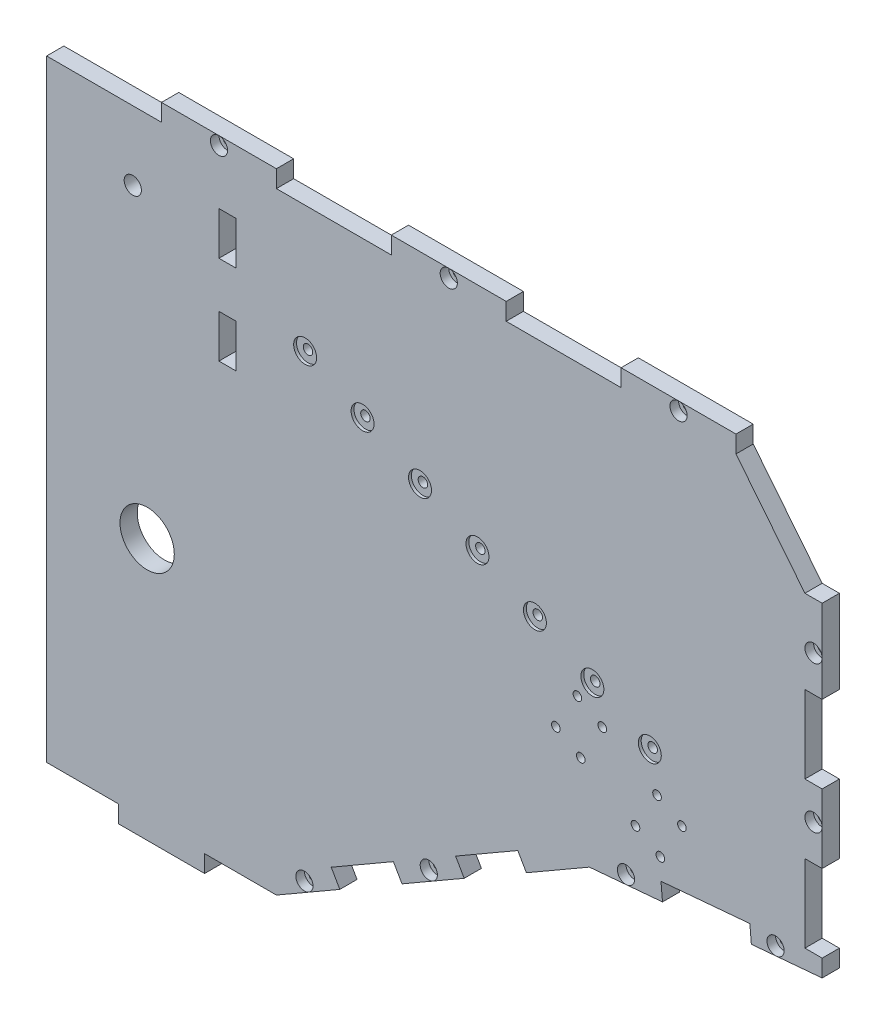
SolidWorks part; units mm, degrees
ref_plane "Plan de face" through (0, 0, 0) normal (0, 0, 1) x (1, 0, 0)
ref_plane "Plan de dessus" through (0, 0, 0) normal (0, 1, 0) x (1, 0, 0)
ref_plane "Plan de droite" through (0, 0, 0) normal (1, 0, 0) x (0, 0, -1)
sketch "Esquisse1" plane through (0, 0, 0) normal (0, 0, 1) x (1, 0, 0)
  line L1 (135, -106.5) -> (-135, -106.5)
  line L2 (135, -106.5) -> (135, 106.5)
  line L3 (135, 106.5) -> (-135, 106.5)
  line L4 (-135, -106.5) -> (-135, 106.5)
  line L5 (135, -106.5) -> (-135, 106.5) construction
  line L6 (135, 106.5) -> (-135, -106.5) construction
  point P0 (0, 0)
extrude "Boss.-Extru.1" add sketch "Esquisse1" along normal blind 6
sketch "Esquisse3" plane through (0, 0, 6) normal (0, 0, 1) x (1, 0, 0)
  line L0 (-135, -106.5) -> (135, -106.5) construction
  line L1 (-135, 106.5) -> (-135, -106.5) construction
  circle A0 centre (-100, -21.5) radius 9.45
  circle A1 centre (58.4592, 0.8811) radius 1.5
  circle A9 centre (49.7989, 5.8811) radius 1.5
  circle A10 centre (42.2989, -7.1093) radius 1.5
  circle A11 centre (50.9592, -12.1093) radius 1.5
  circle A12 centre (70.0118, -23.1093) radius 1.5
  circle A13 centre (78.672, -28.1093) radius 1.5
  circle A14 centre (86.172, -15.1189) radius 1.5
  circle A15 centre (77.5118, -10.1189) radius 1.5
  dimension "D1" = 85
  dimension "D3" = 3
  dimension "D4" = 3
  dimension "D5" = 3
  dimension "D6" = 3
  dimension "D7" = 3
  dimension "D8" = 3
  dimension "D9" = 3
  dimension "D10" = 3
  dimension "D19" = 18.9
  dimension "D2" = 35
  dimension "D11" = 99.3907
  dimension "D12" = 94.3907
  dimension "D13" = 107.3811
  dimension "D14" = 112.3811
  dimension "D15" = 78.3907
  dimension "D16" = 83.3907
  dimension "D17" = 96.3811
  dimension "D18" = 91.3811
extrude "Enlèv. mat.-Extru.1" cut sketch "Esquisse3" against normal blind 10
sketch "Esquisse4" plane through (0, 0, 6) normal (0, 0, 1) x (1, 0, 0)
  line L1 (-135, -106.5) -> (135, -106.5) construction
  line L3 (-135, 106.5) -> (-135, -106.5) construction
  circle A0 centre (-105, 82.5) radius 3
  dimension "D1" = 189
  dimension "D2" = 30
extrude "Enlèv. mat.-Extru.2" cut sketch "Esquisse4" against normal blind 10
sketch "Esquisse5" plane through (0, 0, 6) normal (0, 0, 1) x (1, 0, 0)
  line L0 (53.9637, -43.5898) -> (135, -36.5)
  line L1 (53.9637, -43.5898) -> (-55, -106.5)
  line L3 (135, -106.5) -> (135, 106.5) construction
  line L4 (-135, -106.5) -> (135, -106.5) construction
  dimension "D1" = 80
  dimension "D2" = 95
  dimension "D3" = 0
  dimension "D4" = 150
  dimension "D5" = 70
  dimension "D6" = 0
extrude "Enlèv. mat.-Extru.11" cut sketch "Esquisse5" against normal through all and the other way through all
sketch "Esquisse7" plane through (0, 0, 6) normal (0, 0, 1) x (1, 0, 0)
  line L0 (135, -36.5) -> (135, 106.5) construction
  line L1 (135, 106.5) -> (129, 106.5)
  line L2 (135, 106.5) -> (135, 76.5)
  line L3 (135, 76.5) -> (129, 76.5)
  line L4 (129, 106.5) -> (129, 76.5)
  line L6 (135, -3.5) -> (129, -3.5)
  line L7 (135, -3.5) -> (135, -30.5)
  line L8 (135, -30.5) -> (129, -30.5)
  line L9 (135, 20.5) -> (129, 20.5)
  line L10 (135, 20.5) -> (135, 47.5)
  line L11 (135, 47.5) -> (129, 47.5)
  line L12 (129, 20.5) -> (129, 47.5)
  line L13 (129, -3.5) -> (129, -30.5)
  dimension "D1" = 24
  dimension "D2" = 29
  dimension "D3" = 27
  dimension "D4" = 30
  dimension "D5" = 27
  dimension "D6" = 6
  dimension "D7" = 6
extrude "Enlèv. mat.-Extru.13" cut sketch "Esquisse7" against normal blind 10
sketch "Esquisse8" plane through (0, 106.5, 0) normal (0, 1, 0) x (1, 0, 0)
  line L0 (129, -6) -> (-135, -6) construction
  line L1 (105, -6) -> (65, -6)
  line L2 (105, -6) -> (105, 0)
  line L3 (105, 0) -> (65, 0)
  line L4 (65, -6) -> (65, 0)
  line L5 (129, 0) -> (-135, 0) construction
  line L8 (25, -6) -> (-15, -6)
  line L9 (25, -6) -> (25, 0)
  line L10 (25, 0) -> (-15, 0)
  line L11 (-15, -6) -> (-15, 0)
  line L12 (-55, -6) -> (-95, -6)
  line L13 (-55, -6) -> (-55, 0)
  line L14 (-55, 0) -> (-95, 0)
  line L15 (-95, -6) -> (-95, 0)
  dimension "D1" = 40
  dimension "D2" = 40
  dimension "D3" = 40
  dimension "D4" = 40
  dimension "D5" = 40
  dimension "D6" = 40
extrude "Boss.-Extru.2" add sketch "Esquisse8" along normal blind 6
sketch "Esquisse9" plane through (0, 0, 0) normal (0, 0, -1) x (-1, 0, 0)
  line L0 (-110.35, -38.6566) -> (-79.4137, -41.3632)
  line L1 (-78.8908, -35.386) -> (-109.8271, -32.6794)
  line L2 (-53.9637, -43.5898) -> (-135, -36.5) construction
  line L3 (-79.4137, -41.3632) -> (-78.8908, -35.386)
  line L4 (-109.8271, -32.6794) -> (-110.35, -38.6566)
  dimension "D1" = 25.45
  dimension "D2" = 24.65
  dimension "D3" = 6
  dimension "D4" = 6
extrude "Enlèv. mat.-Extru.14" cut sketch "Esquisse9" against normal blind 10
sketch "Esquisse10" plane through (0, 0, 0) normal (0, 0, -1) x (-1, 0, 0)
  line L0 (-32.0356, -56.25) -> (-10.3849, -68.75)
  line L1 (55, -106.5) -> (-53.9637, -43.5898) construction
  line L2 (-10.3849, -68.75) -> (-7.3849, -63.5538)
  line L3 (-7.3849, -63.5538) -> (-29.0356, -51.0538)
  line L4 (-29.0356, -51.0538) -> (-32.0356, -56.25)
  line L5 (11.2657, -81.25) -> (32.9164, -93.75)
  line L6 (32.9164, -93.75) -> (35.9164, -88.5538)
  line L7 (35.9164, -88.5538) -> (14.2657, -76.0538)
  line L8 (14.2657, -76.0538) -> (11.2657, -81.25)
  dimension "D1" = 25
  dimension "D2" = 25
  dimension "D3" = 25
  dimension "D4" = 25.5
  dimension "D5" = 6
  dimension "D6" = 6
extrude "Enlèv. mat.-Extru.15" cut sketch "Esquisse10" against normal blind 6
sketch "Esquisse11" plane through (0, 0, 0) normal (0, 0, -1) x (-1, 0, 0)
  line L0 (135, -106.5) -> (55, -106.5) construction
  line L1 (69, 59.5) -> (75, 59.5)
  line L2 (69, 59.5) -> (69, 44.5)
  line L3 (69, 44.5) -> (75, 44.5)
  line L4 (75, 59.5) -> (75, 44.5)
  line L5 (135, 106.5) -> (135, -106.5) construction
  line L7 (69, 90.5) -> (75, 90.5)
  line L8 (69, 90.5) -> (69, 75.5)
  line L9 (69, 75.5) -> (75, 75.5)
  line L10 (75, 90.5) -> (75, 75.5)
  dimension "D1" = 6
  dimension "D2" = 15
  dimension "D3" = 151
  dimension "D4" = 60
  dimension "D5" = 15
  dimension "D6" = 16
extrude "Enlèv. mat.-Extru.16" cut sketch "Esquisse11" against normal blind 10
sketch "Esquisse12" plane through (0, 0, 6) normal (0, 0, 1) x (1, 0, 0)
  line L0 (-15, 112.5) -> (25, 112.5) construction
  line L1 (135, 47.5) -> (135, 76.5) construction
  line L2 (-95, 112.5) -> (-55, 112.5) construction
  line L3 (135, -3.5) -> (135, 20.5) construction
  line L4 (65, 112.5) -> (105, 112.5) construction
  circle A0 centre (-25, 52.5) radius 1.65
  circle A1 centre (35, 22.5) radius 1.65
  circle A2 centre (-5, 42.5) radius 1.65
  circle A3 centre (15, 32.5) radius 1.65
  circle A4 centre (55, 12.5) radius 1.65
  circle A5 centre (75, 2.5) radius 1.65
  circle A6 centre (-45, 62.5) radius 1.65
  dimension "D4" = 3.3
  dimension "D6" = 100
  dimension "D7" = 3.3
  dimension "D8" = 3.3
  dimension "D9" = 3.3
  dimension "D10" = 3.3
  dimension "D11" = 60
  dimension "D12" = 110
  dimension "D13" = 80
  dimension "D14" = 100
  dimension "D15" = 80
  dimension "D16" = 120
  dimension "D17" = 140
  dimension "D18" = 70
  dimension "D2" = 3.3
  dimension "D3" = 3.3
  dimension "D19" = 160
  dimension "D20" = 60
  dimension "D21" = 180
  dimension "D22" = 50
  dimension "D5" = 90
extrude "Enlèv. mat.-Extru.17" cut sketch "Esquisse12" against normal through all
sketch "Esquisse14" plane through (0, -106.5, 0) normal (0, -1, 0) x (1, 0, 0)
  line L0 (-135, 0) -> (-55, 0) construction
  line L1 (-110, 0) -> (-80, 0)
  line L2 (-110, 0) -> (-110, 6)
  line L3 (-110, 6) -> (-80, 6)
  line L4 (-80, 0) -> (-80, 6)
  line L5 (-135, 6) -> (-55, 6) construction
  dimension "D1" = 30
  dimension "D2" = 25
extrude "Boss.-Extru.3" add sketch "Esquisse14" along normal blind 6
sketch "Esquisse15" plane through (0, 0, 6) normal (0, 0, 1) x (1, 0, 0)
  line L0 (105, 106.5) -> (129, 106.5)
  line L1 (129, 106.5) -> (129, 76.5)
  line L2 (129, 76.5) -> (105, 106.5)
extrude "Enlèv. mat.-Extru.18" cut sketch "Esquisse15" against normal through all
sketch "Esquisse16" plane through (0, 0, 6) normal (0, 0, 1) x (1, 0, 0)
  circle A0 centre (-45, 62.5) radius 4
  circle A1 centre (-25, 52.5) radius 4
  circle A2 centre (-5, 42.5) radius 4
  circle A3 centre (15, 32.5) radius 4
  circle A4 centre (35, 22.5) radius 4
  circle A5 centre (55, 12.5) radius 4
  circle A6 centre (75, 2.5) radius 4
  dimension "D1" = 8
  dimension "D2" = 8
  dimension "D3" = 8
  dimension "D4" = 8
  dimension "D5" = 8
  dimension "D6" = 8
  dimension "D7" = 8
extrude "Enlèv. mat.-Extru.19" cut sketch "Esquisse16" against normal blind 1
sketch "Esquisse17" plane through (0, 0, 6) normal (0, 0, 1) x (1, 0, 0)
  line L0 (-95, 112.5) -> (-55, 112.5) construction
  line L1 (135, 47.5) -> (135, 76.5) construction
  line L2 (-11.2657, -81.25) -> (10.3849, -68.75) construction
  line L3 (110.35, -38.6566) -> (135, -36.5) construction
  line L4 (-95, 112.5) -> (-95, 106.5) construction
  line L5 (-15, 112.5) -> (-15, 106.5) construction
  line L6 (65, 112.5) -> (65, 106.5) construction
  line L7 (135, -3.5) -> (129, -3.5) construction
  line L8 (135, 47.5) -> (129, 47.5) construction
  line L9 (-14.2657, -76.0538) -> (-11.2657, -81.25) construction
  line L10 (53.9637, -43.5898) -> (79.4137, -41.3632) construction
  line L11 (-55, -106.5) -> (-32.9164, -93.75) construction
  line L12 (78.8908, -35.386) -> (79.4137, -41.3632) construction
  line L13 (-32.9164, -93.75) -> (-35.9164, -88.5538) construction
  circle A0 centre (-75, 109.5) radius 2.995
  circle A1 centre (5, 109.5) radius 2.995
  circle A2 centre (85, 109.5) radius 2.995
  circle A3 centre (132, 60) radius 2.995
  circle A4 centre (132, 9) radius 2.995
  circle A5 centre (-1.9404, -72.4019) radius 2.995
  circle A6 centre (118.7817, -34.9075) radius 2.995
  circle A7 centre (66.6998, -39.464) radius 2.995
  circle A8 centre (-45.2417, -97.4019) radius 2.995
  point P24 (-15, 109.5)
  point P27 (65, 109.5)
  point P34 (-12.7657, -78.6519)
  point P48 (79.1523, -38.3746)
  point P49 (-34.4164, -91.1519)
  dimension "D1" = 5.99
  dimension "D3" = 5.99
  dimension "D4" = 5.99
  dimension "D5" = 5.99
  dimension "D7" = 5.99
  dimension "D10" = 5.99
  dimension "D11" = 5.99
  dimension "D18" = 5.99
  dimension "D19" = 5.99
  dimension "D2" = 3
  dimension "D6" = 3
  dimension "D8" = 3
  dimension "D9" = 3
  dimension "D12" = 20
  dimension "D13" = 20
  dimension "D14" = 20
  dimension "D15" = 12.5
  dimension "D16" = 12.5
  dimension "D17" = 12.5
  dimension "D20" = 3
  dimension "D21" = 3
  dimension "D22" = 12.5
  dimension "D23" = 12.5
extrude "Enlèv. mat.-Extru.20" cut sketch "Esquisse17" against normal blind 3
sketch "Esquisse18" plane through (0, 0, 6) normal (0, 0, 1) x (1, 0, 0)
  circle A0 centre (-75, 109.5) radius 1.5
  circle A1 centre (5, 109.5) radius 1.5
  circle A2 centre (85, 109.5) radius 1.5
  circle A3 centre (132, 60) radius 1.5
  circle A4 centre (132, 9) radius 1.5
  circle A5 centre (118.7817, -34.9075) radius 1.5
  circle A6 centre (66.6998, -39.464) radius 1.5
  circle A7 centre (-1.9404, -72.4019) radius 1.5
  circle A8 centre (-45.2417, -97.4019) radius 1.5
extrude "Enlèv. mat.-Extru.21" cut sketch "Esquisse18" against normal blind 13
